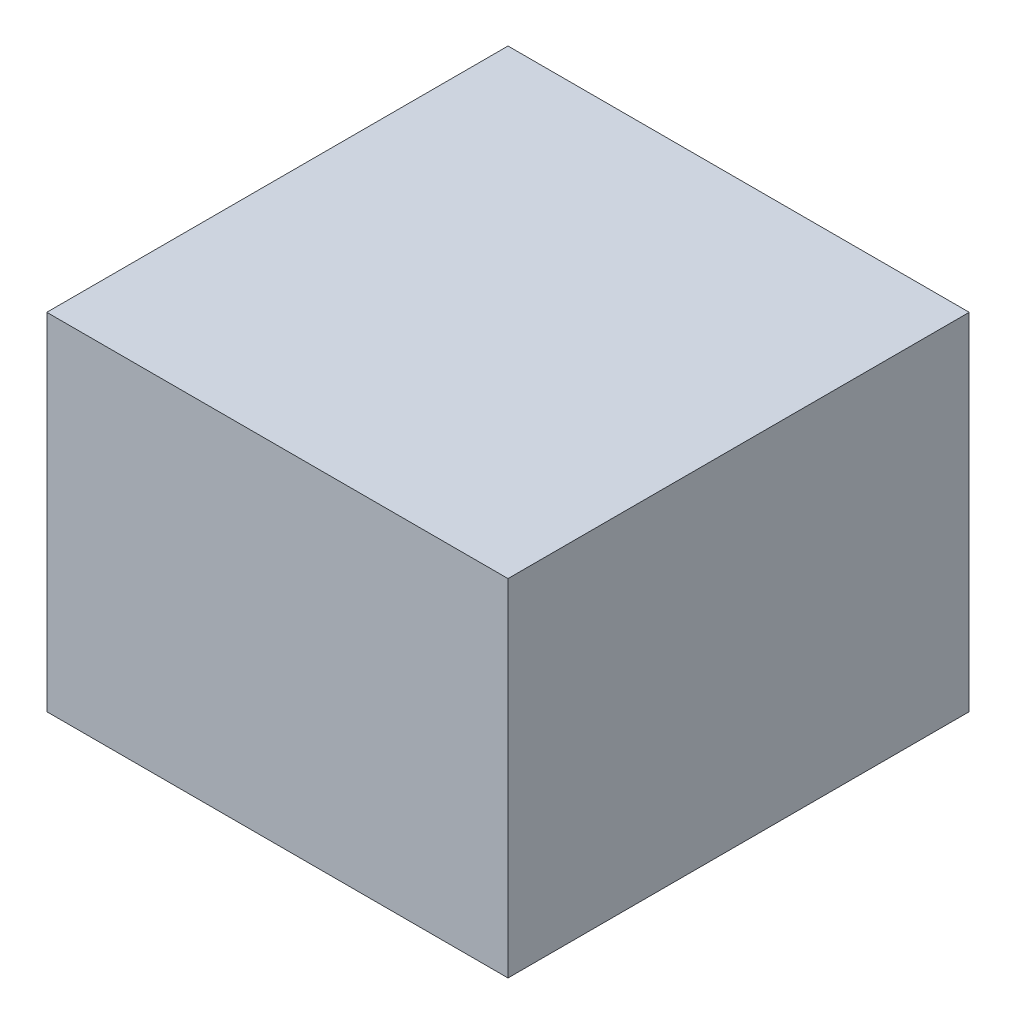
SolidWorks part; units mm, degrees
ref_plane "Front Plane" through (0, 0, 0) normal (0, 0, 1) x (1, 0, 0)
ref_plane "Top Plane" through (0, 0, 0) normal (0, 1, 0) x (1, 0, 0)
ref_plane "Right Plane" through (0, 0, 0) normal (1, 0, 0) x (0, 0, -1)
other "Configuration Table"
sketch "Sketch1" plane through (0, 0, 0) normal (0, 0, 1) x (1, 0, 0)
  line L1 (420, 862) -> (460, 862)
  line L2 (420, 862) -> (420, 892)
  line L3 (420, 892) -> (460, 892)
  line L4 (460, 862) -> (460, 892)
extrude "OVEN_sicak_dolap_termostat_1" add sketch "Sketch1" against normal blind 40 from offset 340 separate body
